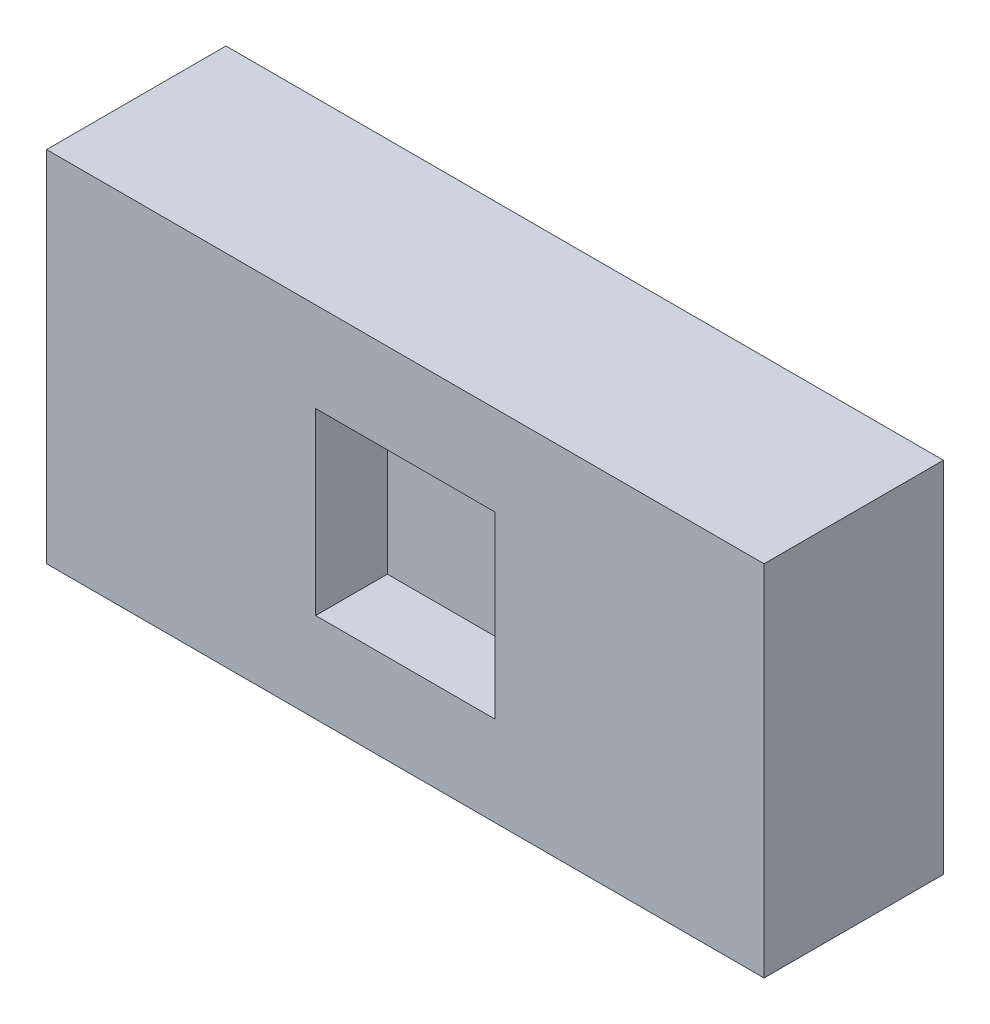
SolidWorks part; units mm, degrees
ref_plane "Front Plane" through (0, 0, 0) normal (0, 0, 1) x (1, 0, 0)
ref_plane "Top Plane" through (0, 0, 0) normal (0, 1, 0) x (1, 0, 0)
ref_plane "Right Plane" through (0, 0, 0) normal (1, 0, 0) x (0, 0, -1)
sketch "RectangleSketch" plane through (0, 0, 0) normal (0, 0, 1) x (1, 0, 0)
  line L1 (0, 0) -> (40, 0)
  line L2 (0, 0) -> (0, 20)
  line L3 (0, 20) -> (40, 20)
  line L4 (40, 0) -> (40, 20)
  dimension "width_mm" = 40
  dimension "height_mm" = 20
extrude "BlindBoss" add sketch "RectangleSketch" along normal blind 10 separate body
sketch "CutSketch" plane through (0, 0, 10) normal (0, 0, 1) x (1, 0, 0)
  line L1 (15, 5) -> (25, 5)
  line L2 (15, 5) -> (15, 15)
  line L3 (15, 15) -> (25, 15)
  line L4 (25, 5) -> (25, 15)
  dimension "cut_width_mm" = 10
  dimension "cut_height_mm" = 10
  dimension "cut_left_mm" = 15
  dimension "cut_bottom_mm" = 5
extrude "BlindCut" cut sketch "CutSketch" against normal blind 4
equation "\"cut_left_mm@CutSketch\" = (\"width_mm@RectangleSketch\" - \"cut_width_mm@CutSketch\") / 2"
equation "\"cut_bottom_mm@CutSketch\" = (\"height_mm@RectangleSketch\" - \"cut_height_mm@CutSketch\") / 2"
